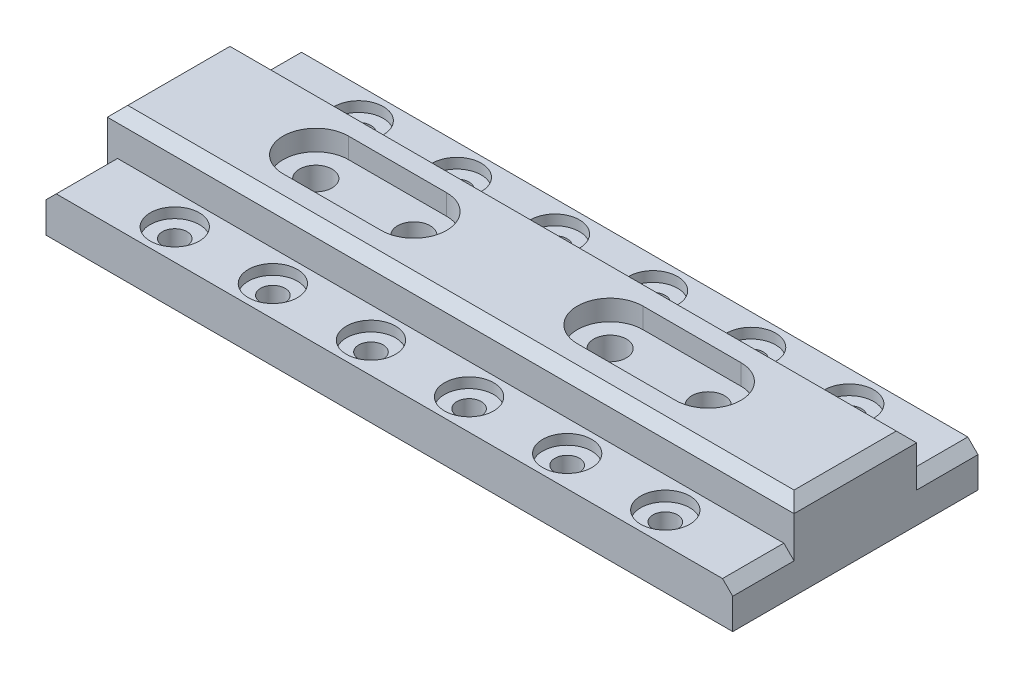
SolidWorks part; units mm, degrees
material "Brass"
ref_plane "Front Plane" through (0, 0, 0) normal (0, 0, 1) x (1, 0, 0)
ref_plane "Top Plane" through (0, 0, 0) normal (0, 1, 0) x (1, 0, 0)
ref_plane "Right Plane" through (0, 0, 0) normal (1, 0, 0) x (0, 0, -1)
sketch "Sketch1" plane through (0, 0, 0) normal (1, 0, 0) x (0, 0, -1)
  line L0 (0, 32.0316) -> (0, -34.6089) construction
  line L1 (0, 55) -> (0, -55) construction
  line L2 (38.1, 0) -> (-38.1, 0)
  line L3 (55, 0) -> (-55, 0) construction
  line L4 (-38.1, 0) -> (-38.1, 12.7)
  line L5 (38.1, 0) -> (38.1, 12.7)
  line L6 (-38.1, 12.7) -> (-19.05, 12.7)
  line L7 (38.1, 12.7) -> (19.05, 12.7)
  line L8 (-19.05, 12.7) -> (-19.05, 25.4)
  line L9 (19.05, 12.7) -> (19.05, 25.4)
  line L10 (-19.05, 25.4) -> (19.05, 25.4)
  point P10 (0, 0)
  point P16 (0, 25.4)
  dimension "D1" = 76.2
  dimension "D2" = 38.1
  dimension "D3" = 12.7
  dimension "D4" = 25.4
extrude "Boss-Extrude1" add sketch "Sketch1" along normal mid plane 213.36
sketch "Sketch3" plane through (0, 12.7, 0) normal (0, 1, 0) x (1, 0, 0)
  line L0 (-76.2, -28.575) -> (-45.72, -28.575) construction
  line L1 (-77.6808, 0) -> (111.1807, 0) construction
  line L2 (-13.97, 0) -> (13.97, 0) construction
  circle A0 centre (-76.2, -28.575) radius 3.81
  circle A1 centre (-45.72, -28.575) radius 3.81
  circle A2 centre (-15.24, -28.575) radius 3.81
  circle A3 centre (15.24, -28.575) radius 3.81
  circle A4 centre (45.72, -28.575) radius 3.81
  circle A5 centre (76.2, -28.575) radius 3.81
  circle A6 centre (76.2, 28.575) radius 3.81
  circle A7 centre (45.72, 28.575) radius 3.81
  circle A8 centre (15.24, 28.575) radius 3.81
  circle A9 centre (-15.24, 28.575) radius 3.81
  circle A10 centre (-45.72, 28.575) radius 3.81
  circle A11 centre (-76.2, 28.575) radius 3.81
  dimension "D3" = 7.62
  dimension "D1" = 76.2
  dimension "D2" = 28.575
  dimension "D5" = 30.48
  dimension "D4" = 6
extrude "Cut-Extrude1" cut sketch "Sketch3" against normal through all
sketch "Sketch5" plane through (0, 12.7, 0) normal (0, 1, 0) x (1, 0, 0)
  line L0 (-76.2, -28.575) -> (-45.72, -28.575) construction
  line L1 (-76.2, -28.575) -> (-76.2, 28.575) construction
  circle A0 centre (-76.2, -28.575) radius 7.62
  circle A1 centre (-45.72, -28.575) radius 7.62
  circle A2 centre (-15.24, -28.575) radius 7.62
  circle A3 centre (15.24, -28.575) radius 7.62
  circle A4 centre (45.72, -28.575) radius 7.62
  circle A5 centre (76.2, -28.575) radius 7.62
  circle A6 centre (-45.72, 28.575) radius 7.62
  circle A7 centre (-15.24, 28.575) radius 7.62
  circle A8 centre (15.24, 28.575) radius 7.62
  circle A9 centre (45.72, 28.575) radius 7.62
  circle A10 centre (76.2, 28.575) radius 7.62
  circle A11 centre (-76.2, 28.575) radius 7.62
  dimension "D1" = 15.24
  dimension "D4" = 90
  dimension "D5" = 30.48
  dimension "D6" = 57.15
  dimension "D2" = 6
  dimension "D3" = 2
extrude "Cut-Extrude2" cut sketch "Sketch5" against normal blind 3.175
sketch "Sketch6" plane through (0, 25.4, 0) normal (0, 1, 0) x (1, 0, 0)
  line L0 (-13.97, 0) -> (13.97, 0) construction
  line L1 (0, -13.97) -> (0, 13.97) construction
  line L2 (-60.96, 0) -> (-30.48, 0) construction
  line L3 (0, 40.2969) -> (0, -42.239) construction
  circle A0 centre (-60.96, 0) radius 5.08
  circle A1 centre (-30.48, 0) radius 5.08
  circle A2 centre (30.48, 0) radius 5.08
  circle A3 centre (60.96, 0) radius 5.08
  dimension "D2" = 10.16
  dimension "D1" = 60.96
  dimension "D4" = 30.48
  dimension "D3" = 2
extrude "Cut-Extrude3" cut sketch "Sketch6" against normal through all
sketch "Sketch7" plane through (0, 25.4, 0) normal (0, 1, 0) x (1, 0, 0)
  line L0 (-60.96, 0) -> (-30.48, 0) construction
  line L1 (-60.96, 10.16) -> (-30.48, 10.16)
  line L2 (-60.96, -10.16) -> (-30.48, -10.16)
  line L3 (30.48, 0) -> (60.96, 0) construction
  line L4 (30.48, 10.16) -> (60.96, 10.16)
  line L5 (30.48, -10.16) -> (60.96, -10.16)
  arc A0 (-60.96, 10.16) -> (-60.96, -10.16) centre (-60.96, 0) ccw
  arc A1 (-30.48, -10.16) -> (-30.48, 10.16) centre (-30.48, 0) ccw
  arc A2 (30.48, 10.16) -> (30.48, -10.16) centre (30.48, 0) ccw
  arc A3 (60.96, -10.16) -> (60.96, 10.16) centre (60.96, 0) ccw
  point P4 (-45.72, 0)
  point P13 (45.72, 0)
  dimension "D1" = 20.32
  dimension "D2" = 20.32
extrude "Cut-Extrude4" cut sketch "Sketch7" against normal blind 6.35
chamfer "Chamfer1" distance 3.175 angle 45 8 edges at (-106.68, 12.7, -28.575) (-106.68, 12.7, 28.575) (106.68, 12.7, -28.575) (106.68, 12.7, 28.575) (-106.68, 25.4, 0) (0, 25.4, -19.05) (106.68, 25.4, 0) (0, 25.4, 19.05)
